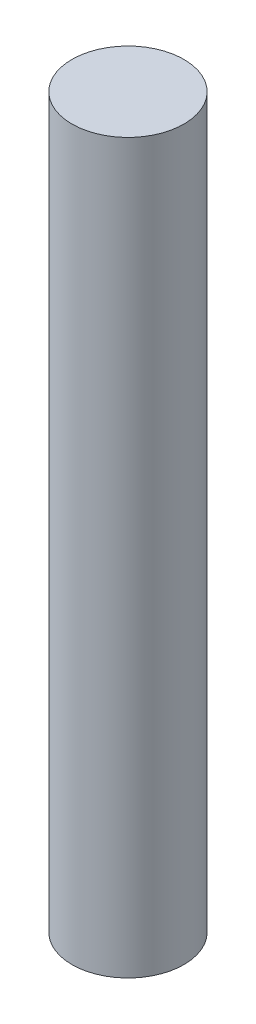
SolidWorks part; units mm, degrees
ref_plane "Front Plane" through (0, 0, 0) normal (0, 0, 1) x (1, 0, 0)
ref_plane "Top Plane" through (0, 0, 0) normal (0, 1, 0) x (1, 0, 0)
ref_plane "Right Plane" through (0, 0, 0) normal (1, 0, 0) x (0, 0, -1)
sketch "Sketch1" plane through (0, 0, 0) normal (0, 1, 0) x (1, 0, 0)
  circle A0 centre (0, 0) radius 5
  dimension "D1" = 10
extrude "Boss-Extrude1" add sketch "Sketch1" along normal mid plane 65
